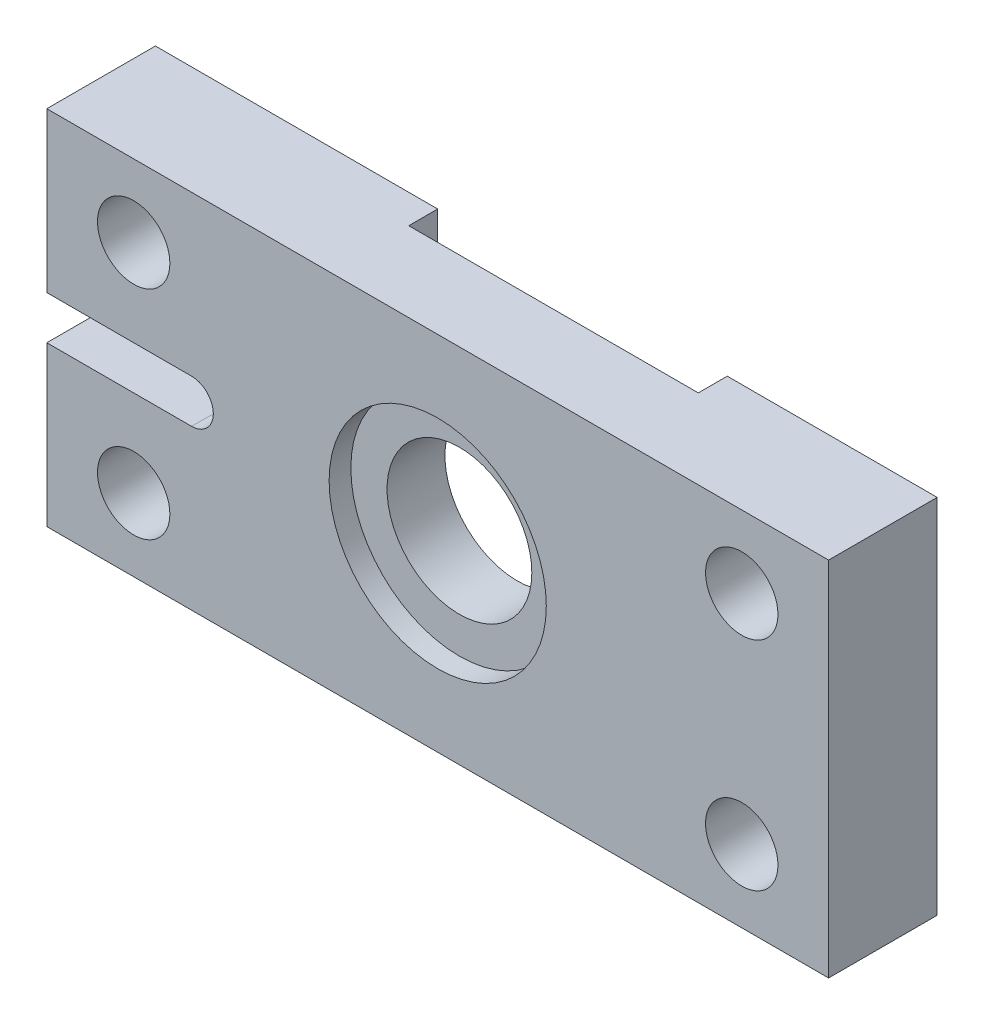
SolidWorks part; units mm, degrees
ref_plane "Plano frontal" through (0, 0, 0) normal (0, 0, 1) x (1, 0, 0)
ref_plane "Plano superior" through (0, 0, 0) normal (0, 1, 0) x (1, 0, 0)
ref_plane "Plano direito" through (0, 0, 0) normal (1, 0, 0) x (0, 0, -1)
sketch "Esboço1" plane through (0, 0, 0) normal (0, 0, 1) x (1, 0, 0)
  line L1 (-54, 25) -> (54, 25)
  line L2 (-54, 25) -> (-54, -25)
  line L3 (-54, -25) -> (54, -25)
  line L4 (54, 25) -> (54, -25)
  line L5 (-54, 25) -> (54, -25) construction
  line L6 (-54, -25) -> (54, 25) construction
  point P0 (0, 0)
  dimension "D1" = 108
extrude "Ressalto-extrusão1" add sketch "Esboço1" along normal blind 15
sketch "Esboço2" plane through (0, 0, 0) normal (0, 0, 1) x (1, 0, 0)
  line L4 (-34, 3) -> (-54, 3)
  line L6 (-54, 25) -> (-54, -25) construction
  line L7 (-34, -3) -> (-54, -3)
  line L8 (-54, 3) -> (-54, -3)
  circle A0 centre (0, 0) radius 10
  circle A1 centre (42, 15) radius 5
  circle A2 centre (-42, 15) radius 5
  circle A3 centre (42, -15) radius 5
  circle A5 centre (-42, -15) radius 5
  arc A6 (-34, -3) -> (-34, 3) centre (-34, 0) ccw
  dimension "D1" = 20
extrude "Corte-extrusão2" cut sketch "Esboço2" along normal blind 15
sketch "Esboço4" plane through (0, 0, 15) normal (0, 0, 1) x (1, 0, 0)
  circle A0 centre (0, 0) radius 15
extrude "Corte-extrusão5" cut sketch "Esboço4" against normal blind 3 contours A0
sketch "Esboço5" plane through (0, -25, 0) normal (0, -1, 0) x (1, 0, 0)
  line L0 (-15, 0) -> (-15, 4)
  line L2 (-54, 0) -> (54, 0) construction
  line L3 (25, 0) -> (-15, 0)
  line L4 (-15, 4) -> (25, 4)
  line L5 (25, 4) -> (25, 0)
extrude "Corte-extrusão6" cut sketch "Esboço5" against normal through all
